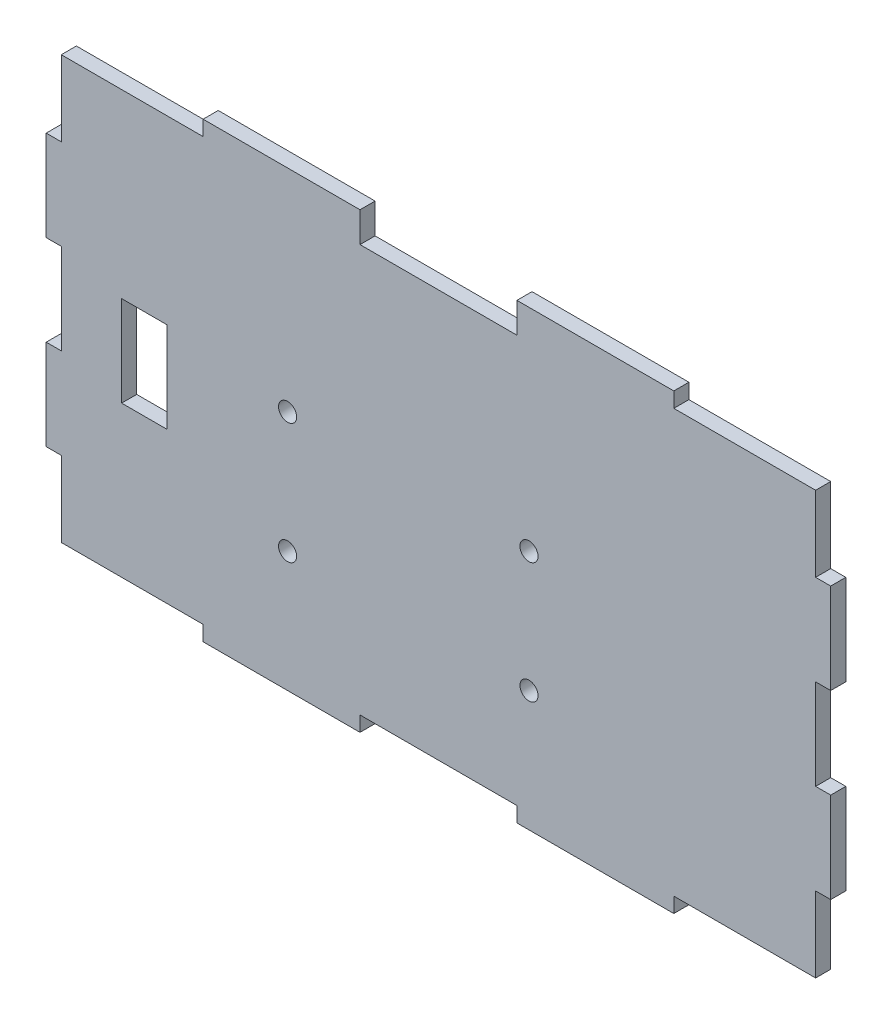
SolidWorks part; units mm, degrees
ref_plane "Alzado" through (0, 0, 0) normal (0, 0, 1) x (1, 0, 0)
ref_plane "Planta" through (0, 0, 0) normal (0, 1, 0) x (1, 0, 0)
ref_plane "Vista lateral" through (0, 0, 0) normal (1, 0, 0) x (0, 0, -1)
sketch "Croquis1" plane through (0, 0, 0) normal (0, 0, 1) x (1, 0, 0)
  line L0 (130, 150) -> (130, 129.9372) construction
  line L1 (52, 0) -> (104, 0)
  line L2 (0, 30) -> (0, 60)
  line L3 (52, 150) -> (104, 150)
  line L4 (260, 30) -> (260, 60)
  line L5 (0, 75) -> (16.5526, 75) construction
  line L6 (0, 120) -> (5, 120)
  line L7 (0, 90) -> (0, 120)
  line L8 (5, 90) -> (0, 90)
  line L9 (0, 30) -> (5, 30)
  line L10 (0, 0) -> (5, 0) construction
  line L11 (5, 60) -> (0, 60)
  line L12 (5, 30) -> (5, 5)
  line L13 (5, 60) -> (5, 90)
  line L14 (5, 120) -> (5, 145)
  line L15 (0, 30) -> (0, 0) construction
  line L16 (255, 30) -> (255, 5)
  line L17 (260, 30) -> (255, 30)
  line L18 (255, 60) -> (260, 60)
  line L19 (255, 60) -> (255, 90)
  line L20 (255, 90) -> (260, 90)
  line L21 (260, 120) -> (255, 120)
  line L22 (255, 120) -> (255, 145)
  line L23 (260, 90) -> (260, 120)
  line L24 (52, 150) -> (52, 145)
  line L25 (208, 5) -> (255, 5)
  line L26 (104, 145) -> (104, 150)
  line L27 (208, 150) -> (208, 145)
  line L28 (156, 145) -> (156, 150)
  line L29 (208, 0) -> (208, 5)
  line L30 (52, 145) -> (5, 145)
  line L31 (104, 145) -> (156, 145)
  line L32 (208, 145) -> (255, 145)
  line L33 (156, 150) -> (208, 150)
  line L34 (156, 5) -> (156, 0)
  line L35 (104, 5) -> (156, 5)
  line L36 (104, 5) -> (104, 0)
  line L37 (52, 0) -> (52, 5)
  line L38 (52, 5) -> (5, 5)
  line L39 (156, 0) -> (208, 0)
  line L40 (0, 0) -> (52, 0) construction
  dimension "D1" = 5
  dimension "D2" = 260
  dimension "D3" = 5
  dimension "D4" = 30
  dimension "D5" = 30
  dimension "D6" = 52
  dimension "D7" = 52
  dimension "D8" = 5
  dimension "D9" = 150
  dimension "D10" = 52
  dimension "D11" = 25
extrude "Saliente-Extruir1" add sketch "Croquis1" along normal blind 5
sketch "Croquis2" plane through (0, 0, 5) normal (0, 0, 1) x (1, 0, 0)
  line L0 (156, 150) -> (156, 145) construction
  line L1 (104, 145) -> (156, 145)
  line L2 (104, 145) -> (104, 140)
  line L3 (104, 140) -> (156, 140)
  line L4 (156, 145) -> (156, 140)
  dimension "D1" = 5
extrude "Cortar-Extruir1" cut sketch "Croquis2" against normal blind 10
sketch "Croquis3" plane through (0, 0, 5) normal (0, 0, 1) x (1, 0, 0)
  line L1 (20, 130) -> (240, 130)
  line L2 (20, 130) -> (20, 20)
  line L3 (20, 20) -> (240, 20)
  line L4 (240, 130) -> (240, 20)
  line L5 (5, 90) -> (5, 60) construction
  line L6 (255, 60) -> (255, 90) construction
  line L8 (208, 5) -> (255, 5) construction
  line L9 (80, 40) -> (160, 40) construction
  line L10 (160, 40) -> (160, 80) construction
  line L11 (160, 80) -> (80, 80) construction
  line L12 (80, 80) -> (80, 40) construction
  line L13 (255, 145) -> (208, 145) construction
  line L14 (55, 50) -> (105, 50)
  line L15 (135, 50) -> (185, 50)
  line L16 (20, 110) -> (240, 110) construction
  line L17 (55, 90) -> (105, 90)
  line L18 (80, 80) -> (80, 90) construction
  line L19 (160, 80) -> (160, 90) construction
  line L20 (135, 90) -> (185, 90)
  circle A0 centre (160, 40) radius 3
  circle A1 centre (80, 40) radius 3
  circle A2 centre (80, 80) radius 3
  circle A3 centre (160, 80) radius 3
  text T0 "Temperature " font "Century Gothic" height in points 20
  text T1 "Skin conduct." font "Century Gothic" height in points 22
  text T2 "E-health monitor" font "Century Gothic" height in points 36
  text T3 "ECG" font "Century Gothic" height in points 26
  text T4 "EMG" font "Century Gothic" height in points 26
  point P23 (80, 50)
  point P27 (160, 50)
  point P33 (80, 90)
  point P38 (160, 90)
  dimension "D1" = 6
  dimension "D6" = 40
  dimension "D2" = 15
  dimension "D3" = 15
  dimension "D4" = 15
  dimension "D5" = 15
  dimension "D7" = 80
  dimension "D8" = 60
  dimension "D9" = 20
  dimension "D10" = 50
  dimension "D11" = 10
  dimension "D12" = 50
  dimension "D13" = 20
  dimension "D14" = 50
  dimension "D15" = 10
  dimension "D16" = 50
  dimension "D17" = 10
extrude "Cortar-Extruir2" cut sketch "Croquis3" against normal blind 10 contours A2 | A1 | A0 | A3
sketch "Croquis4" plane through (0, 0, 5) normal (0, 0, 1) x (1, 0, 0)
  line L0 (20, 20) -> (240, 20) construction
  line L1 (25, 85) -> (40, 85)
  line L2 (25, 85) -> (25, 55)
  line L3 (25, 55) -> (40, 55)
  line L4 (40, 85) -> (40, 55)
  line L5 (20, 130) -> (20, 20) construction
  dimension "D1" = 15
  dimension "D2" = 35
  dimension "D3" = 30
  dimension "D4" = 5
extrude "Cortar-Extruir3" cut sketch "Croquis4" against normal blind 10
